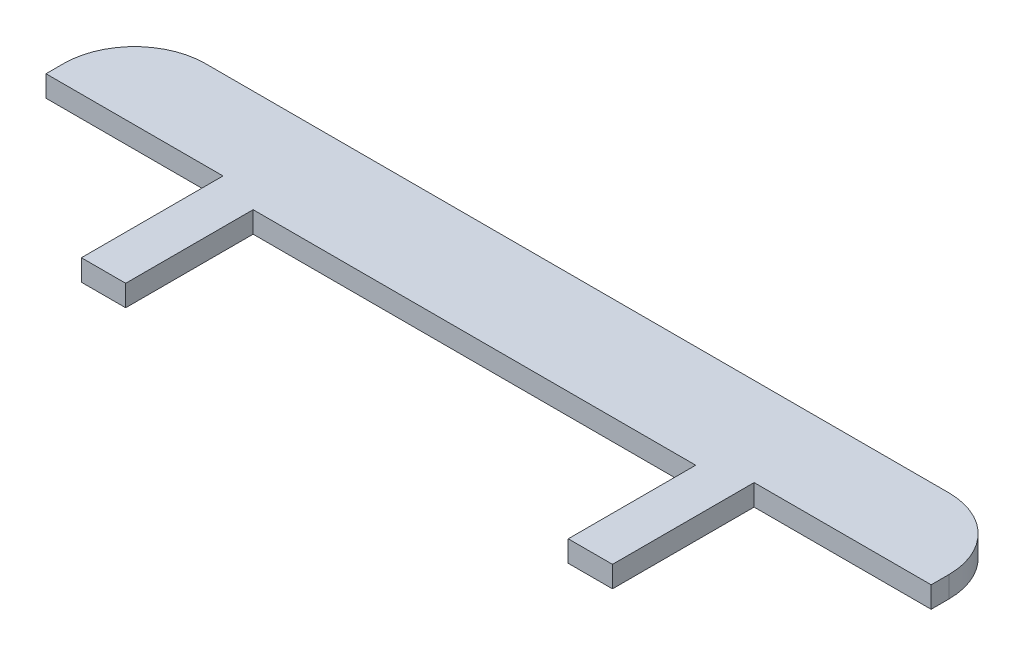
SolidWorks part; units mm, degrees
material "7050-T7651"
ref_plane "Front Plane" through (0, 0, 0) normal (0, 0, 1) x (1, 0, 0)
ref_plane "Top Plane" through (0, 0, 0) normal (0, 1, 0) x (1, 0, 0)
ref_plane "Right Plane" through (0, 0, 0) normal (1, 0, 0) x (0, 0, -1)
sketch "Sketch1" plane through (0, 0, 0) normal (0, 1, 0) x (1, 0, 0)
  line L0 (19.05, 0) -> (31.75, 0)
  line L1 (-31.75, 0) -> (-19.05, 0)
  line L2 (-31.75, 0) -> (-31.75, 6.35)
  line L3 (-31.75, 6.35) -> (31.75, 6.35)
  line L4 (31.75, 0) -> (31.75, 6.35)
  line L6 (-19.05, 0) -> (-19.05, -10.16)
  line L7 (-19.05, -10.16) -> (-15.875, -10.16)
  line L8 (19.05, 0) -> (19.05, -10.16)
  line L9 (15.875, -10.16) -> (19.05, -10.16)
  line L11 (-15.875, -10.16) -> (-15.875, -1.016)
  line L12 (-15.875, -1.016) -> (15.875, -1.016)
  line L13 (15.875, -10.16) -> (15.875, -1.016)
  point P4 (0, 6.35)
  point P11 (0, -1.016)
  dimension "D1" = 63.5
  dimension "D2" = 6.35
  dimension "D3" = 38.1
  dimension "D4" = 10.16
  dimension "D5" = 1.016
  dimension "D6" = 3.175
extrude "Boss-Extrude1" add sketch "Sketch1" along normal blind 1.524
fillet "Fillet1" radius 5.08 2 edges at (31.75, 0.762, -6.35) (-31.75, 0.762, -6.35)
